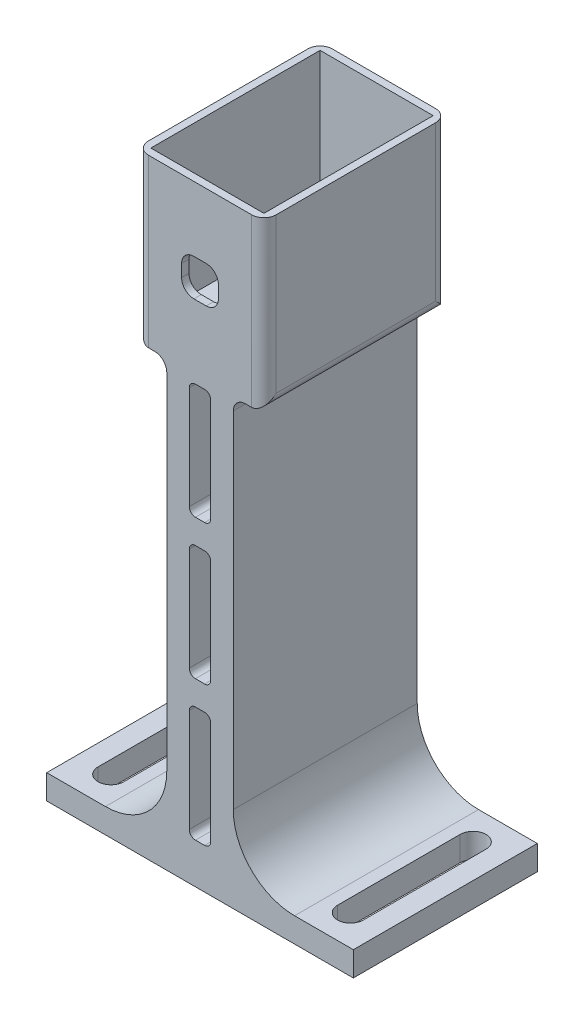
SolidWorks part; units mm, degrees
material "PLA"
ref_plane "Alzado" through (0, 0, 0) normal (0, 0, 1) x (1, 0, 0)
ref_plane "Planta" through (0, 0, 0) normal (0, 1, 0) x (1, 0, 0)
ref_plane "Vista lateral" through (0, 0, 0) normal (1, 0, 0) x (0, 0, -1)
sketch "Croquis1" plane through (0, 0, 0) normal (0, 0, 1) x (1, 0, 0)
  line L1 (-6.2283, 28.5194) -> (-10.3826, 28.5194)
  line L2 (-6.2283, 28.5194) -> (-6.2283, -55.4806)
  line L3 (-6.2283, -55.4806) -> (-10.3826, -55.4806)
  line L4 (-10.3826, 28.5194) -> (-10.3826, -55.4806)
  line L5 (-10.3826, 18.0194) -> (14.6174, 18.0194)
  line L6 (-10.3826, 18.0194) -> (-10.3826, -55.4806)
  line L7 (-10.3826, -55.4806) -> (14.6174, -55.4806)
  line L8 (14.6174, 18.0194) -> (14.6174, -55.4806)
  dimension "D1" = 84
  dimension "D2" = 73.5
  dimension "D3" = 25
extrude "Saliente-Extruir1" add sketch "Croquis1" against normal blind 30 contours L8 L5 L4 L7
sketch "Croquis2" plane through (0, 18.0194, 0) normal (0, 1, 0) x (1, 0, 0)
  line L0 (-6.2283, 30) -> (-6.2283, 0) construction
  line L1 (-6.2283, 30) -> (14.6174, 30)
  line L2 (-6.2283, 30) -> (-6.2283, 0)
  line L3 (-6.2283, 0) -> (14.6174, 0)
  line L4 (14.6174, 30) -> (14.6174, 0)
  line L5 (-4.8055, 7) -> (13.1945, 7)
  line L6 (-4.8055, 7) -> (-4.8055, 5)
  line L7 (-4.8055, 5) -> (13.1945, 5)
  line L8 (13.1945, 7) -> (13.1945, 5)
  line L9 (-4.8055, 7) -> (13.1945, 5) construction
  line L10 (-4.8055, 5) -> (13.1945, 7) construction
  point P6 (4.1945, 6)
  point P11 (0, 0)
  point P12 (4.1945, 0)
  point P15 (0, 0)
  dimension "D1" = 2
  dimension "D2" = 18
  dimension "D3" = 5
extrude "Saliente-Extruir2" add sketch "Croquis2" along normal blind 2
sketch "Croquis3" plane through (0, 20.0194, 0) normal (0, 1, 0) x (1, 0, 0)
  line L1 (-6.2283, 30) -> (14.6174, 30)
  line L2 (-6.2283, 30) -> (-6.2283, 0)
  line L3 (-6.2283, 0) -> (14.6174, 0)
  line L4 (14.6174, 30) -> (14.6174, 0)
  line L5 (-5.0283, 28.8) -> (13.4174, 28.8)
  line L6 (-5.0283, 28.8) -> (-5.0283, 1.2)
  line L7 (-5.0283, 1.2) -> (13.4174, 1.2)
  line L8 (13.4174, 28.8) -> (13.4174, 1.2)
  dimension "D1" = 1.2
  dimension "D2" = 1.2
  dimension "D3" = 1.2
  dimension "D4" = 1.2
extrude "Saliente-Extruir3" add sketch "Croquis3" along normal blind 24
sketch "Croquis4" plane through (0, 0, 0) normal (0, 0, 1) x (1, 0, 0)
  line L1 (-5.0283, 20.0194) -> (13.4174, 20.0194) construction
  line L2 (-5.0283, 20.0194) -> (13.4174, 20.0194) construction
  line L3 (4.1945, 20.0194) -> (4.1945, 35.0194) construction
  line L5 (3.1945, 33.4362) -> (5.1945, 33.4362)
  line L6 (1.1945, 31.4362) -> (1.1945, 29.4362)
  line L7 (3.1945, 27.4362) -> (5.1945, 27.4362)
  line L8 (7.1945, 31.4362) -> (7.1945, 29.4362)
  arc A0 (5.1945, 27.4362) -> (7.1945, 29.4362) centre (5.1945, 29.4362) ccw
  arc A1 (1.1945, 29.4362) -> (3.1945, 27.4362) centre (3.1945, 29.4362) ccw
  arc A2 (5.1945, 33.4362) -> (7.1945, 31.4362) centre (5.1945, 31.4362) cw
  arc A3 (3.1945, 33.4362) -> (1.1945, 31.4362) centre (3.1945, 31.4362) ccw
  point P8 (0, 0)
  point P9 (4.1945, 33.4362)
  point P12 (7.1945, 27.4362)
  point P17 (7.1945, 33.4362)
  point P20 (1.1945, 33.4362)
  dimension "D4" = 2
  dimension "D1" = 15
  dimension "D2" = 6
  dimension "D3" = 6
  dimension "D5" = 7.4168
extrude "Cortar-Extruir1" cut sketch "Croquis4" against normal blind 12
sketch "Croquis6" plane through (0, 0, -28.8) normal (0, 0, 1) x (1, 0, 0)
  line L1 (-0.8055, 20.0194) -> (9.1945, 20.0194)
  line L2 (-0.8055, 20.0194) -> (-0.8055, 22.1194)
  line L3 (-0.8055, 22.1194) -> (9.1945, 22.1194)
  line L5 (4.1945, 44.0194) -> (4.1945, 0.2194) construction
  line L12 (9.1945, 20.0194) -> (9.1945, 22.1194)
  line L14 (14.6174, 44.0194) -> (-6.2283, 44.0194) construction
  line L15 (-7.7605, 20.0194) -> (-19.4063, 20.0194) construction
  point P3 (4.1945, 22.1194)
  dimension "D2" = 2.1
  dimension "D3" = 10
extrude "Cortar-Extruir2" cut sketch "Croquis6" against normal blind 12
sketch "Croquis7" plane through (0, 0, 0) normal (0, 0, 1) x (1, 0, 0)
  line L16 (-13.4805, 18.0194) -> (-44.8018, 18.0194) construction
  line L17 (-6.2283, 44.0194) -> (-6.2283, -55.4806) construction
  line L18 (-6.2283, 16.8194) -> (-1.2283, 16.8194)
  line L19 (-6.2283, 16.8194) -> (-6.2283, -55.4806)
  line L20 (-6.2283, -55.4806) -> (-1.2283, -55.4806)
  line L21 (-1.2283, 16.8194) -> (-1.2283, -55.4806)
  line L22 (-6.2283, -55.4806) -> (14.6174, -55.4806) construction
  line L23 (14.6174, 44.0194) -> (14.6174, -55.4806) construction
  line L24 (14.6174, 16.8194) -> (9.6174, 16.8194)
  line L25 (14.6174, 16.8194) -> (14.6174, -55.4806)
  line L26 (14.6174, -55.4806) -> (9.6174, -55.4806)
  line L27 (9.6174, 16.8194) -> (9.6174, -55.4806)
  dimension "D1" = 5
  dimension "D2" = 1.2
extrude "Cortar-Extruir3" cut sketch "Croquis7" against normal blind 81
fillet "Redondeo1" radius 2 8 edges at (9.6174, 16.8194, -15) (14.6174, 16.8194, -15) (14.6174, 30.4194, -30) (-6.2283, 30.4194, -30) (-6.2283, 30.4194, 0) (-1.2283, 16.8194, -15) (-6.2283, 16.8194, -15) (14.6174, 30.4194, 0)
sketch "Croquis9" plane through (0, 0, 0) normal (0, 0, 1) x (1, 0, 0)
  line L0 (-20.8055, -55.4806) -> (29.1945, -55.4806)
  line L2 (-1.2283, -55.4806) -> (9.6174, -55.4806) construction
  line L3 (29.1945, -55.4806) -> (29.1945, -51.4806)
  line L4 (29.1945, -51.4806) -> (19.6174, -51.4806)
  line L5 (-20.8055, -51.4806) -> (-20.8055, -55.4806)
  line L6 (-1.2283, -20.3306) -> (-1.2283, -41.4806)
  line L7 (-1.2283, -55.4806) -> (-1.2283, 14.8194) construction
  line L8 (9.6174, -20.3306) -> (9.6174, -41.4806)
  line L9 (9.6174, 14.8194) -> (9.6174, -55.4806) construction
  line L10 (-11.2283, -51.4806) -> (-20.8055, -51.4806)
  line L11 (-1.2283, -20.3306) -> (9.6174, -20.3306)
  arc A0 (9.6174, -41.4806) -> (19.6174, -51.4806) centre (19.6174, -41.4806) ccw
  arc A1 (-1.2283, -41.4806) -> (-11.2283, -51.4806) centre (-11.2283, -41.4806) cw
  point P3 (4.1945, -55.4806)
  point P6 (4.1945, -55.4806)
  point P18 (9.6174, -51.4806)
  point P21 (-1.2283, -51.4806)
  dimension "D3" = 10
  dimension "D1" = 50
  dimension "D2" = 4
extrude "Saliente-Extruir4" add sketch "Croquis9" against normal blind 30
sketch "Croquis10" plane through (0, -51.4806, 0) normal (0, 1, 0) x (1, 0, 0)
  line L0 (26.6945, 30) -> (26.6945, 0) construction
  line L1 (29.1945, 30) -> (19.6174, 30) construction
  line L2 (29.1945, 0) -> (19.6174, 0) construction
  line L3 (29.1945, 30) -> (29.1945, 0) construction
  line L4 (23.7247, 25) -> (23.7247, 5) construction
  line L5 (25.8247, 25) -> (25.8247, 5)
  line L6 (21.6247, 25) -> (21.6247, 5)
  line L7 (4.1945, 30) -> (4.1945, 0) construction
  line L8 (12.6174, 30) -> (-4.2283, 30) construction
  line L9 (-4.2283, 0) -> (12.6174, 0) construction
  line L10 (-15.3357, 25) -> (-15.3357, 5) construction
  line L11 (-17.4357, 25) -> (-17.4357, 5)
  line L12 (-13.2357, 25) -> (-13.2357, 5)
  arc A0 (25.8247, 25) -> (21.6247, 25) centre (23.7247, 25) ccw
  arc A1 (21.6247, 5) -> (25.8247, 5) centre (23.7247, 5) ccw
  arc A2 (-17.4357, 25) -> (-13.2357, 25) centre (-15.3357, 25) cw
  arc A3 (-13.2357, 5) -> (-17.4357, 5) centre (-15.3357, 5) cw
  point P10 (23.7247, 15)
  point P16 (26.6945, 15)
  point P24 (-15.3357, 15)
  dimension "D2" = 2.1
  dimension "D1" = 2.5
  dimension "D3" = 20
extrude "Cortar-Extruir4" cut sketch "Croquis10" against normal blind 30
sketch "Croquis11" plane through (0, 0, 0) normal (0, 0, 1) x (1, 0, 0)
  line L0 (-20.8055, -55.4806) -> (29.1945, -55.4806) construction
  line L1 (2.4445, 15.5194) -> (5.9445, 15.5194)
  line L2 (2.4445, 15.5194) -> (2.4445, -3.2806)
  line L3 (2.4445, -3.2806) -> (5.9445, -3.2806)
  line L4 (5.9445, 15.5194) -> (5.9445, -3.2806)
  line L5 (2.4445, -7.2806) -> (5.9445, -7.2806)
  line L6 (2.4445, -7.2806) -> (2.4445, -26.0806)
  line L7 (2.4445, -26.0806) -> (5.9445, -26.0806)
  line L8 (5.9445, -7.2806) -> (5.9445, -26.0806)
  line L9 (2.4445, -30.0806) -> (5.9445, -30.0806)
  line L10 (2.4445, -30.0806) -> (2.4445, -48.8806)
  line L11 (2.4445, -48.8806) -> (5.9445, -48.8806)
  line L12 (5.9445, -30.0806) -> (5.9445, -48.8806)
  line L13 (11.6174, 16.8194) -> (24.2426, 16.8194) construction
  line L14 (-11.2283, -51.4806) -> (-20.8055, -51.4806) construction
  point P14 (4.1945, -55.4806)
  point P15 (4.1945, -48.8806)
  dimension "D1" = 3.5
  dimension "D2" = 4
  dimension "D3" = 4
  dimension "D4" = 1.3
  dimension "D5" = 2.6
extrude "Cortar-Extruir5" cut sketch "Croquis11" against normal blind 30
fillet "Redondeo2" radius 1 12 edges at (5.9445, -26.0806, -15) (5.9445, -48.8806, -15) (2.4445, -7.2806, -15) (5.9445, -7.2806, -15) (5.9445, -30.0806, -15) (2.4445, -30.0806, -15) (2.4445, -48.8806, -15) (2.4445, -26.0806, -15) (2.4445, -3.2806, -15) (2.4445, 15.5194, -15) (5.9445, 15.5194, -15) (5.9445, -3.2806, -15)
